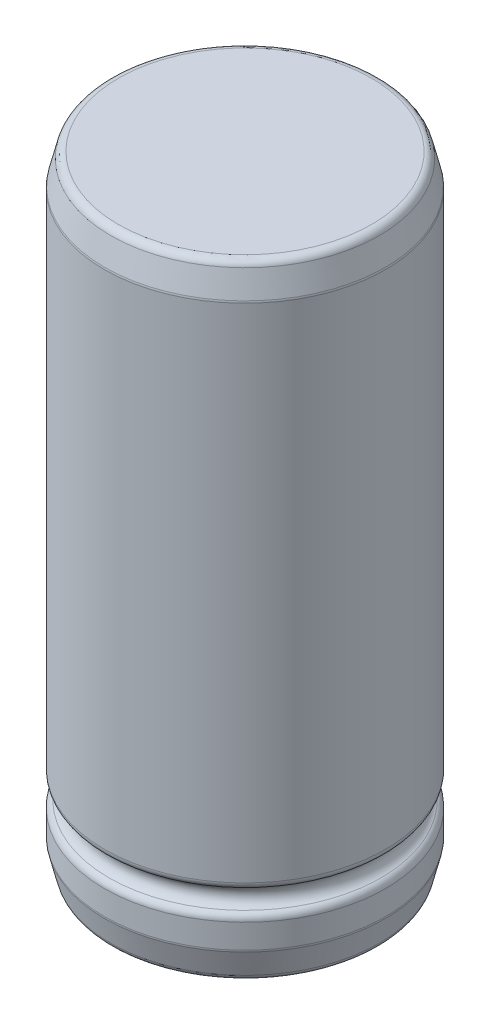
SolidWorks part; units mm, degrees
ref_plane "Přední rovina" through (0, 0, 0) normal (0, 0, 1) x (1, 0, 0)
ref_plane "Horní rovina" through (0, 0, 0) normal (0, 1, 0) x (1, 0, 0)
ref_plane "Pravá rovina" through (0, 0, 0) normal (1, 0, 0) x (0, 0, -1)
sketch "Skica1" plane through (0, 0, 0) normal (0, 0, 1) x (1, 0, 0)
  line L0 (0, 0) -> (0, 80.5016) construction
  line L1 (0, 40) -> (8.5, 40)
  line L2 (9, 38) -> (9, 5.4)
  line L3 (9, 4) -> (9, 2)
  line L4 (8.5, 0) -> (0, 0)
  line L5 (8.5, 40) -> (9, 38)
  line L6 (9, 2) -> (8.5, 0)
  line L7 (0, 0) -> (0, 40)
  arc A0 (9, 5.4) -> (9, 4) centre (9, 4.7) ccw
  point P4 (9, 40)
  point P9 (9, 0)
  dimension "D7" = 0.7
  dimension "D1" = 2
  dimension "D2" = 0.5
  dimension "D3" = 18
  dimension "D4" = 40
  dimension "D5" = 2
  dimension "D6" = 0.5
  dimension "D8" = 4
revolve "Rotovat1" add sketch "Skica1" angle 360 about L0
fillet "Zaoblit1" radius 0.5 6 edges at (0, 4, -9) (0, 5.4, -9) (0, 38, -9) (0, 40, -8.5) (0, 0, -8.5) (0, 2, -9)
sketch "Skica2" plane through (0, 0, 0) normal (0, -1, 0) x (1, 0, 0)
  line L0 (0, 0) -> (0, 5.6408) construction
  circle A0 centre (-3.75, 0) radius 0.4
  circle A1 centre (3.75, 0) radius 0.4
  dimension "D1" = 7.5
  dimension "D2" = 0.8
extrude "Přidat vysunutím1" add sketch "Skica2" along normal blind 3 separate body
